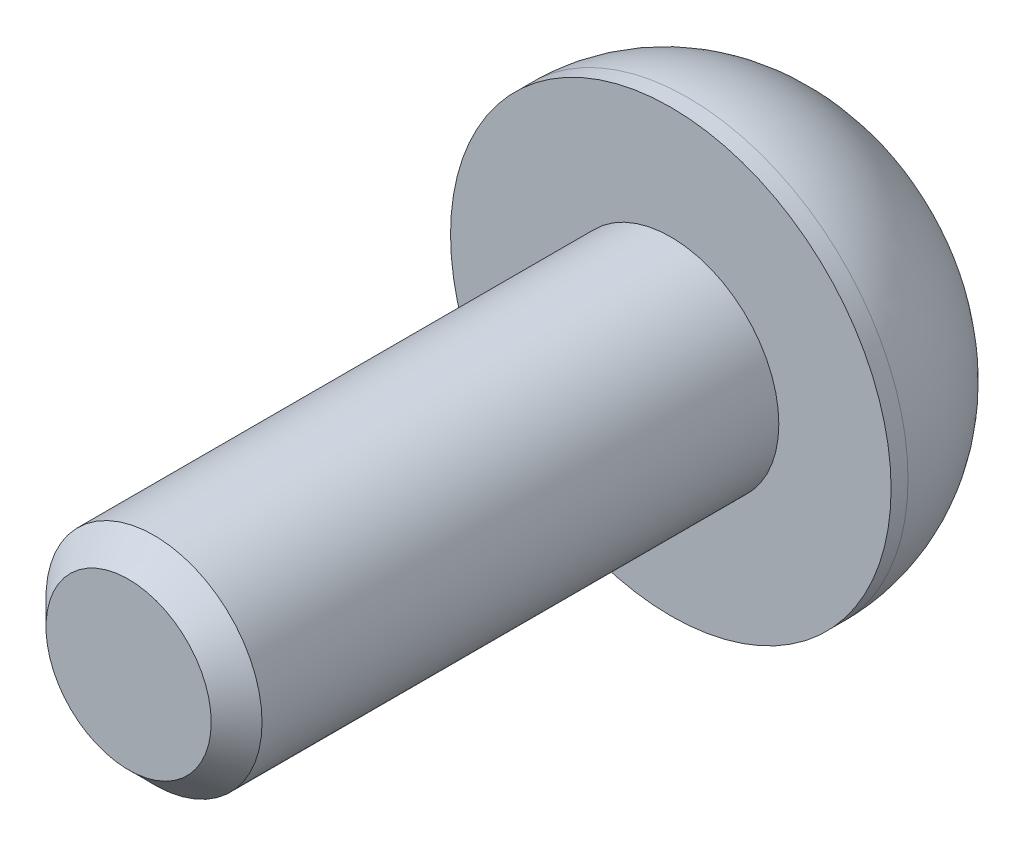
SolidWorks part; units mm, degrees
ref_plane "Přední rovina" through (0, 0, 0) normal (0, 0, 1) x (1, 0, 0)
ref_plane "Horní rovina" through (0, 0, 0) normal (0, 1, 0) x (1, 0, 0)
ref_plane "Pravá rovina" through (0, 0, 0) normal (1, 0, 0) x (0, 0, -1)
sketch "Skica1" plane through (0, 0, 0) normal (0, 0, 1) x (1, 0, 0)
  circle A0 centre (0, 0) radius 2.6
  dimension "D2" = 5.2
extrude "Přidat vysunutím1" add sketch "Skica1" along normal blind 2.2
sketch "Skica2" plane through (0, 0, 2.2) normal (0, 0, 1) x (1, 0, 0)
  circle A0 centre (0, 0) radius 1.275
  dimension "D1" = 2.55
extrude "Přidat vysunutím2" add sketch "Skica2" along normal blind 6.4
fillet "Zaoblit1" radius 2 1 edges at (2.6, 0, 0)
sketch "Skica3" plane through (0, 0, 0) normal (0, 0, -1) x (-1, 0, 0)
  line L0 (0, 3.2614) -> (0, -3.6026) construction
  line L1 (-3.5241, 0) -> (3.8993, 0) construction
  line L2 (-1.65, 0) -> (-1.65, 0.25)
  line L3 (-1.65, 0.25) -> (-0.25, 0.25)
  line L4 (-0.25, 0.25) -> (-0.25, 1.65)
  line L5 (-0.25, 1.65) -> (0.25, 1.65)
  line L6 (0.25, 1.65) -> (0.25, 0.25)
  line L7 (0.25, 0.25) -> (1.65, 0.25)
  line L8 (1.65, 0.25) -> (1.65, -0.25)
  line L9 (0.25, -1.65) -> (0.25, -0.25)
  line L10 (0.25, -0.25) -> (1.65, -0.25)
  line L11 (0.25, -1.65) -> (-0.25, -1.65)
  line L12 (-0.25, -1.65) -> (-0.25, -0.25)
  line L13 (-0.25, -0.25) -> (-1.65, -0.25)
  line L14 (-1.65, -0.25) -> (-1.65, 0)
  dimension "D1" = 0.5
  dimension "D2" = 0.5
  dimension "D3" = 0.5
  dimension "D4" = 0.5
  dimension "D5" = 1.4
  dimension "D6" = 1.4
  dimension "D7" = 1.4
  dimension "D8" = 1.4
extrude "Odebrat vysunutím1" cut sketch "Skica3" against normal blind 0.7
chamfer "Zkosení1" distance 0.3 angle 45 1 edges at (1.275, 0, 8.6)
